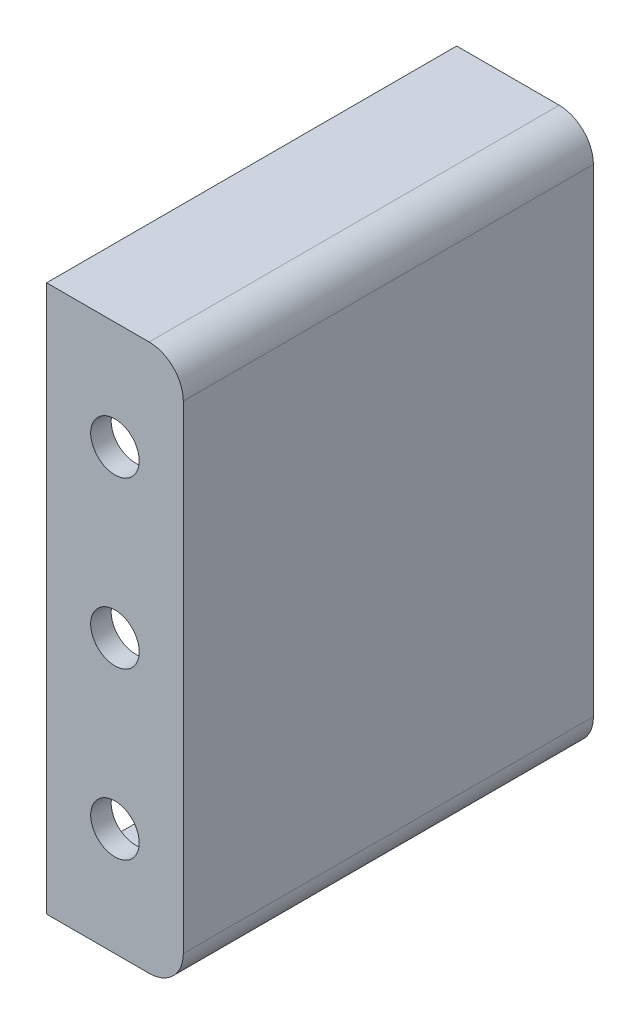
SolidWorks part; units mm, degrees
ref_plane "Front Plane" through (0, 0, 0) normal (1, 0, 0) x (0, 1, 0)
ref_plane "Top Plane" through (0, 0, 0) normal (0, 0, 1) x (0, 1, 0)
ref_plane "Right Plane" through (0, 0, 0) normal (0, 1, 0) x (-1, 0, 0)
sketch "Sketch1" plane through (0, 0, 0) normal (0, 0, 1) x (0, 1, 0)
  line L1 (-40, -10) -> (40, -10)
  line L2 (-40, -10) -> (-40, 10)
  line L3 (-40, 10) -> (40, 10)
  line L4 (40, -10) -> (40, 10)
  line L5 (-40, -10) -> (40, 10) construction
  line L6 (-40, 10) -> (40, -10) construction
  line L7 (0, 10) -> (0, -10) construction
  circle A0 centre (0, 0) radius 3
  point P0 (0, 0)
  dimension "D3" = 6
  dimension "D1" = 20
  dimension "D2" = 80
extrude "Boss-Extrude1" add sketch "Sketch1" along normal blind 60
shell "2 mm top/bot 3 mm side" thickness 3
sketch "Sketch3" plane through (0, 0, 0) normal (0, 0, -1) x (1, 0, 0)
  line L0 (0, 40) -> (0, -40) construction
  line L1 (10, 40) -> (-10, 40) construction
  line L2 (10, -40) -> (-10, -40) construction
  line L3 (0, 40) -> (0, 27.4)
  line L4 (0, -40) -> (0, -27.4)
  circle A0 centre (0, 22.5) radius 4.9
  circle A1 centre (0, 7.5) radius 4.9
  circle A2 centre (0, -7.5) radius 4.9
  circle A3 centre (0, -22.5) radius 4.9
  dimension "D1" = 9.8
  dimension "D2" = 4
extrude "Cut-Extrude1" cut sketch "Sketch3" against normal up to surface (3 mm away) contours L0 A0 | A0 L0 | A1 L0 | L0 A1 | A2 L0 | L0 A2 | L0 A3 | A3 L0 up to face at (-1.5, 1, 3)
sketch "Sketch4" plane through (0, 0, 60) normal (0, 0, 1) x (1, 0, 0)
  line L0 (0, 40) -> (0, -40) construction
  line L1 (10, 40) -> (-10, 40) construction
  line L2 (10, -40) -> (-10, -40) construction
  line L3 (0, 3.55) -> (0, 20.65)
  line L4 (-10, 0) -> (10, 0) construction
  line L5 (-10, -40) -> (-10, 40) construction
  line L6 (10, -40) -> (10, 40) construction
  circle A0 centre (0, 0) radius 3.55
  circle A1 centre (0, 24.2) radius 3.55
  circle A2 centre (0, -24.2) radius 3.55
  dimension "D1" = 7.1
  dimension "D2" = 17.1
extrude "Cut-Extrude3" cut sketch "Sketch4" along direction (0, 0, 1) on the side against the normal blind 10 contours A1 | A0 | A2
fillet "5 mm radius" radius 5 4 edges at (7, 37, 30) (7, -35, 30) (10, -40, 30) (10, 40, 30)
sketch "Sketch7" plane through (0, 40, 0) normal (0, 1, 0) x (-1, 0, 0)
  line L0 (2.5, 60) -> (2.5, 0) construction
  line L1 (-5, 60) -> (10, 60) construction
  line L2 (-5, 0) -> (10, 0) construction
  circle A0 centre (2.5, 30) radius 4.25
  dimension "D1" = 8.5
extrude "8.5 mm hold offset 2 mm" cut sketch "Sketch7" against normal blind 3.2 from offset 2 offset against normal yes
mirror "Mirror1" about plane through (0, 0, 0) normal (0, 1, 0) of "8.5 mm hold offset 2 mm"
